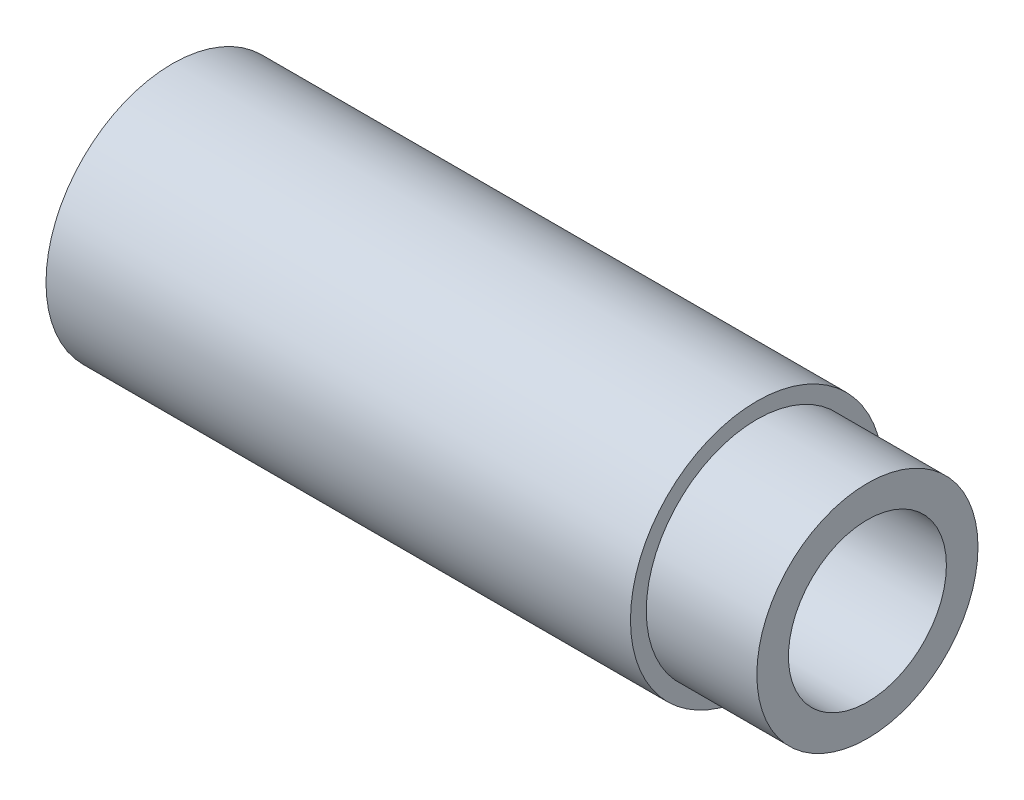
SolidWorks part; units mm, degrees
material "Brass"
ref_plane "Front Plane" through (0, 0, 0) normal (0, 0, 1) x (1, 0, 0)
ref_plane "Top Plane" through (0, 0, 0) normal (0, 1, 0) x (1, 0, 0)
ref_plane "Right Plane" through (0, 0, 0) normal (1, 0, 0) x (0, 0, -1)
sketch "Sketch2" plane through (0, 0, 0) normal (0, 0, 1) x (1, 0, 0)
  line L2 (0, 3.5) -> (-3.5, 3.5)
  line L4 (-22, 2.5) -> (0, 2.5)
  line L5 (0, 2.5) -> (0, 3.5)
  line L6 (0, 0) -> (0, 3.5) construction
  line L7 (0, 0) -> (-8.5778, 0) construction
  line L8 (-3.5, 3.5) -> (-3.5, 4)
  line L9 (-3.5, 4) -> (-22, 4)
  line L10 (-22, 4) -> (-22, 2.5)
  dimension "D1" = 22
  dimension "D2" = 2.5
  dimension "D3" = 3.5
  dimension "D4" = 3.5
  dimension "D7" = 4
revolve "Revolve1" add sketch "Sketch2" angle 360 about L7
